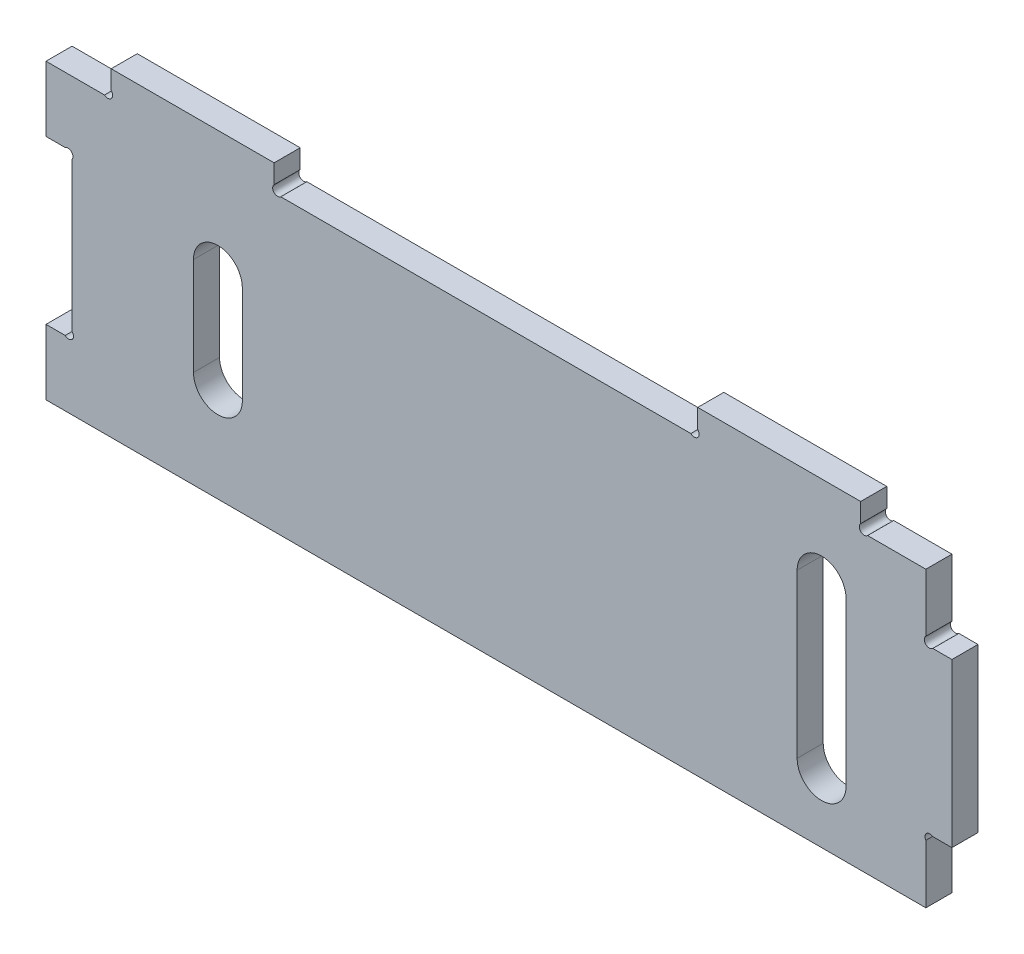
SolidWorks part; units mm, degrees
ref_plane "Plan de face" through (0, 0, 0) normal (0, 0, 1) x (1, 0, 0)
ref_plane "Plan de dessus" through (0, 0, 0) normal (0, 1, 0) x (1, 0, 0)
ref_plane "Plan de droite" through (0, 0, 0) normal (1, 0, 0) x (0, 0, -1)
sketch "Esquisse1" plane through (0, 0, 0) normal (0, 0, 1) x (1, 0, 0)
  line L0 (30.1213, 221.3364) -> (36, 221.3364)
  line L1 (36, 249.3364) -> (36, 121.5955) construction
  line L2 (-242, 241.3364) -> (-224.0494, 241.3364)
  line L4 (-242, 241.3364) -> (-242, 221.3364)
  line L5 (-242, 151.3364) -> (28, 151.3364)
  line L6 (28, 241.3364) -> (28, 223.525)
  line L7 (36, 221.3364) -> (36, 171.3364)
  line L8 (36, 171.3364) -> (30.1213, 171.3364)
  line L9 (28, 169.2824) -> (28, 151.3364)
  line L10 (-242, 221.3364) -> (-236.1213, 221.3364)
  line L11 (-234, 219.2824) -> (-234, 173.525)
  line L12 (-236.1213, 171.4037) -> (-242, 171.4037)
  line L13 (-242, 171.4037) -> (-242, 151.3364)
  line L14 (-222, 243.525) -> (-222, 249.3364)
  line L15 (-222, 249.3364) -> (-172, 249.3364)
  line L16 (-172, 249.3364) -> (-172, 243.525)
  line L17 (8, 243.4577) -> (8, 249.3364)
  line L18 (8, 249.3364) -> (-42, 249.3364)
  line L19 (-42, 249.3364) -> (-42, 243.4577)
  line L20 (-169.9506, 241.3364) -> (-44.1213, 241.3364)
  line L21 (10.1213, 241.3364) -> (28, 241.3364)
  line L22 (-242, 249.3364) -> (-242, 118.9308) construction
  line L48 (-242, 249.3364) -> (36, 249.3364) construction
  line L106 (-242, 241.3364) -> (28, 241.3364) construction
  arc A0 (28, 223.525) -> (30.1213, 221.3364) centre (29.0607, 222.4307) ccw
  arc A1 (-44.1213, 241.3364) -> (-42, 243.4577) centre (-43.0607, 242.397) ccw
  arc A2 (8, 243.4577) -> (10.1213, 241.3364) centre (9.0607, 242.397) ccw
  arc A3 (30.1213, 171.3364) -> (28, 169.2824) centre (29.2451, 170.1189) ccw
  arc A4 (-224.0494, 241.3364) -> (-222, 243.525) centre (-223.0607, 242.4644) ccw
  arc A5 (-172, 243.525) -> (-169.9506, 241.3364) centre (-170.9393, 242.4644) ccw
  arc A6 (-234, 219.2824) -> (-236.1213, 221.3364) centre (-235.2451, 220.1189) ccw
  arc A7 (-236.1213, 171.4037) -> (-234, 173.525) centre (-235.0607, 172.4644) ccw
  dimension "D3" = 20
  dimension "D5" = 20
  dimension "D7" = 50
  dimension "D8" = 1.5
  dimension "D9" = 1.5
  dimension "D10" = 8
  dimension "D11" = 90
  dimension "D12" = 8
  dimension "D13" = 20
  dimension "D14" = 20
  dimension "D1" = 278
  dimension "D4" = 20
  dimension "D6" = 50
  dimension "D28" = 8
extrude "Boss.-Extru.1" add sketch "Esquisse1" along normal blind 8
sketch "Esquisse2" plane through (0, 0, 8) normal (0, 0, 1) x (1, 0, 0)
  line L0 (-4, 221.3364) -> (-4, 171.3364) construction
  line L1 (3.5, 221.3364) -> (3.5, 171.3364)
  line L2 (-11.5, 221.3364) -> (-11.5, 171.3364)
  line L3 (36, 171.3364) -> (36, 221.3364) construction
  line L4 (-234, 219.2824) -> (-234, 173.525) construction
  line L7 (-189.262, 211.254) -> (-189.238, 181.254) construction
  line L8 (-196.762, 211.248) -> (-196.738, 181.248)
  line L9 (-181.762, 211.26) -> (-181.738, 181.26)
  arc A0 (3.5, 221.3364) -> (-11.5, 221.3364) centre (-4, 221.3364) ccw
  arc A1 (-11.5, 171.3364) -> (3.5, 171.3364) centre (-4, 171.3364) ccw
  arc A2 (-196.762, 211.248) -> (-181.762, 211.26) centre (-189.262, 211.254) cw
  arc A3 (-181.738, 181.26) -> (-196.738, 181.248) centre (-189.238, 181.254) cw
  point P2 (-4, 196.3364)
  point P17 (-189.25, 196.254)
  dimension "D1" = 40
  dimension "D2" = 44.75
  dimension "D3" = 30
extrude "Enlèv. mat.-Extru.1" cut sketch "Esquisse2" against normal blind 8
